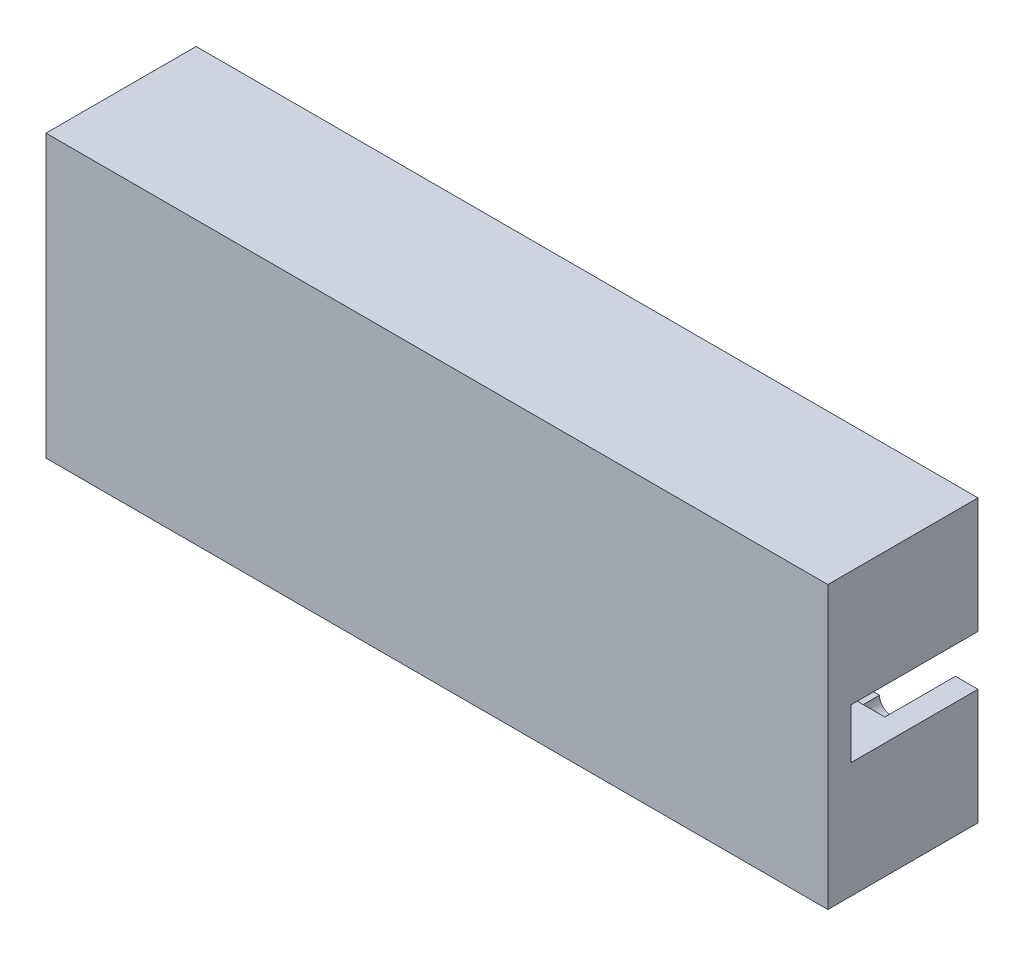
SolidWorks part; units mm, degrees
material "STEEL"
ref_plane "Front Plane" through (0, 0, 0) normal (0, 0, 1) x (1, 0, 0)
ref_plane "Top Plane" through (0, 0, 0) normal (0, 1, 0) x (1, 0, 0)
ref_plane "Right Plane" through (0, 0, 0) normal (1, 0, 0) x (0, 0, -1)
sketch "Sketch1" plane through (0, 0, 0) normal (0, 0, 1) x (1, 0, 0)
  line L1 (-79.375, -28.575) -> (79.375, -28.575)
  line L2 (-79.375, -28.575) -> (-79.375, 28.575)
  line L3 (-79.375, 28.575) -> (79.375, 28.575)
  line L4 (79.375, -28.575) -> (79.375, 28.575)
  line L5 (0, 28.575) -> (0, -28.575) construction
  line L6 (-79.375, 0) -> (79.375, 0) construction
  line L7 (64.135, -16.129) -> (-68.453, -16.129) construction
  line L8 (64.135, -16.129) -> (64.135, 16.129) construction
  line L9 (64.135, 16.129) -> (-68.453, 16.129) construction
  line L10 (-68.453, -16.129) -> (-68.453, 16.129) construction
  line L11 (-2.159, 16.129) -> (-2.159, -16.129) construction
  line L12 (64.135, 0) -> (-68.453, 0) construction
  point P0 (0, 0)
  point P4 (-2.159, 0)
  dimension "D1" = 15.24
  dimension "D2" = 10.922
  dimension "D3" = 32.258
  dimension "D4" = 132.588
  dimension "D5" = 12.446
  dimension "D6" = 57.15
  dimension "D7" = 158.75
extrude "Boss-Extrude1" add sketch "Sketch1" along normal blind 29.591
sketch "Sketch2" plane through (0, 0, 0) normal (0, 0, -1) x (-1, 0, 0)
  line L1 (-64.135, -16.129) -> (68.453, -16.129)
  line L2 (-64.135, -16.129) -> (-64.135, 16.129)
  line L3 (-64.135, 16.129) -> (68.453, 16.129)
  line L4 (68.453, -16.129) -> (68.453, 16.129)
extrude "Cut-Extrude1" cut sketch "Sketch2" against normal through all
sketch "Sketch4" plane through (0, 0, 0) normal (0, 0, -1) x (-1, 0, 0)
  line L0 (-74.803, 5.08) -> (-89.535, 5.08)
  line L1 (-64.135, -16.129) -> (-64.135, 16.129) construction
  line L2 (-89.535, 5.08) -> (-89.535, 3.5)
  line L3 (-89.535, 3.5) -> (-79.375, 3.5)
  line L4 (-79.375, -28.575) -> (-79.375, 28.575) construction
  line L5 (-79.375, 3.5) -> (-79.375, 0)
  line L6 (-79.375, 0) -> (-64.135, 0)
  line L7 (-64.135, 0) -> (-64.135, 5.08)
  line L9 (-64.135, 16.129) -> (-74.803, 16.129)
  line L10 (-64.135, 16.129) -> (-64.135, 5.08)
  line L12 (-74.803, 16.129) -> (-74.803, 5.08)
  point P8 (-89.535, 4.29)
  dimension "D1" = 3.5
  dimension "D2" = 25.4
  dimension "D3" = 5.08
  dimension "D4" = 10.668
extrude "Cut-Extrude2" cut sketch "Sketch4" against normal offset from surface (14.351 mm away) 15.24 up to face at (-2.159, 0, 29.591)
mirror "Mirror1" about plane through (0, 0, 0) normal (0, 1, 0) of "Cut-Extrude2"
fillet "Fillet1" radius 2.3813 2 edges at (74.803, -16.129, 7.1755) (74.803, 16.129, 7.1755)
sketch "Sketch8" plane through (0, 0, 0) normal (0, 0, -1) x (-1, 0, 0)
  line L0 (-64.135, -16.129) -> (-64.135, 16.129) construction
  line L1 (-79.375, -5.08) -> (-64.135, -5.08)
  line L2 (-79.375, -5.08) -> (-79.375, 5.08)
  line L3 (-79.375, 5.08) -> (-64.135, 5.08)
  line L4 (-64.135, -5.08) -> (-64.135, 5.08)
  point P5 (-79.375, 5.08)
  point P7 (-64.135, 5.08)
extrude "Cut-Extrude5" cut sketch "Sketch8" against normal offset from surface (25.781 mm away) 3.81 up to face at (-2.159, 0, 29.591)
sketch "Sketch5" plane through (0, 0, 29.591) normal (0, 0, 1) x (1, 0, 0)
  line L1 (-79.375, 28.575) -> (79.375, 28.575)
  line L2 (-79.375, 28.575) -> (-79.375, -28.575)
  line L3 (-79.375, -28.575) -> (79.375, -28.575)
  line L4 (79.375, 28.575) -> (79.375, -28.575)
extrude "Boss-Extrude2" add sketch "Sketch5" along normal blind 0.889
sketch "Sketch6" plane through (0, 0, 0) normal (0, 0, -1) x (-1, 0, 0)
  line L0 (-61.7537, -16.129) -> (-61.7537, 16.129) construction
  line L1 (79.375, 0) -> (-79.375, 0) construction
  line L2 (-64.135, 16.129) -> (68.453, 16.129) construction
  line L3 (-64.135, -16.129) -> (-64.135, 16.129)
  line L4 (-59.3725, -16.129) -> (-59.3725, 16.129)
  line L5 (2.159, 0) -> (2.159, 16.129) construction
  line L6 (66.0718, -16.129) -> (66.0718, 16.129) construction
  line L7 (68.453, -16.129) -> (68.453, 16.129)
  line L8 (63.6905, -16.129) -> (63.6905, 16.129)
  arc A0 (-64.135, -16.129) -> (-59.3725, -16.129) centre (-61.7537, -16.129) ccw
  arc A1 (-59.3725, 16.129) -> (-64.135, 16.129) centre (-61.7537, 16.129) ccw
  arc A2 (-72.4217, 16.129) -> (-74.803, 13.7478) centre (-72.4217, 13.7478) ccw construction
  arc A3 (68.453, -16.129) -> (63.6905, -16.129) centre (66.0718, -16.129) cw
  arc A4 (63.6905, 16.129) -> (68.453, 16.129) centre (66.0718, 16.129) cw
  point P6 (-61.7537, 0)
  point P21 (66.0718, 0)
extrude "Cut-Extrude3" cut sketch "Sketch6" against normal up to surface (29.591 mm away) up to face at (-2.159, 0, 29.591)
other "Move Face1" [suppressed] parameters "D1"=12.065
sketch "Sketch7" plane through (0, 0, 0) normal (0, 0, -1) x (-1, 0, 0)
  line L0 (79.375, 0) -> (-79.375, 0) construction
  line L1 (79.375, -28.575) -> (79.375, 28.575) construction
  circle A0 centre (31.75, 0) radius 20
  dimension "D1" = 40
  dimension "D2" = 47.625
extrude "Cut-Extrude4" cut sketch "Sketch7" against normal blind 5
